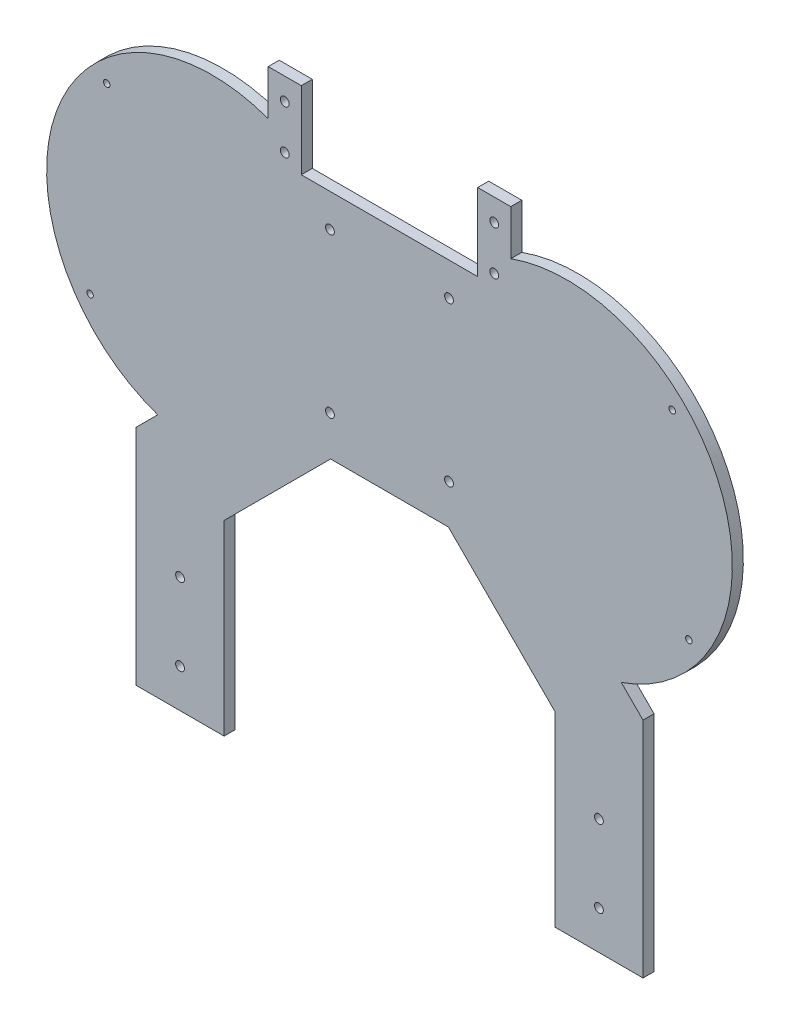
SolidWorks part; units mm, degrees
ref_plane "Front Plane" through (0, 0, 0) normal (0, 0, 1) x (1, 0, 0)
ref_plane "Top Plane" through (0, 0, 0) normal (0, 1, 0) x (1, 0, 0)
ref_plane "Right Plane" through (0, 0, 0) normal (1, 0, 0) x (0, 0, -1)
sketch "Sketch1" plane through (0, 0, 0) normal (0, 0, 1) x (1, 0, 0)
  line L1 (-100, -75) -> (100, -75)
  line L2 (-100, -75) -> (-100, 75)
  line L3 (-100, 75) -> (100, 75)
  line L4 (100, -75) -> (100, 75)
  line L5 (-100, -75) -> (100, 75) construction
  line L6 (-100, 75) -> (100, -75) construction
  line L8 (-47.5, 40) -> (47.5, 40) construction
  line L9 (0, 75) -> (0, -75) construction
  line L10 (-27, -52) -> (27, -52) construction
  line L11 (-27, -52) -> (-27, 20) construction
  line L12 (-27, 20) -> (27, 20) construction
  line L13 (27, -52) -> (27, 20) construction
  line L14 (-27, -52) -> (27, 20) construction
  line L15 (-27, 20) -> (27, -52) construction
  line L23 (-55, 70) -> (55, 70)
  line L24 (-55, 70) -> (-55, -70)
  line L25 (-55, -70) -> (55, -70)
  line L26 (55, 70) -> (55, -70)
  line L27 (-55, 70) -> (55, -70) construction
  line L28 (-55, -70) -> (55, 70) construction
  line L29 (-40, 70) -> (40, 70)
  line L30 (-40, 70) -> (-40, 35)
  line L31 (-40, 35) -> (40, 35)
  line L32 (40, 70) -> (40, 35)
  line L33 (-40, 70) -> (40, 35) construction
  line L34 (-40, 35) -> (40, 70) construction
  circle A2 centre (-47.5, 40) radius 2
  circle A3 centre (47.5, 40) radius 2
  circle A4 centre (-27, 20) radius 2
  circle A5 centre (27, 20) radius 2
  circle A6 centre (27, -52) radius 2
  circle A7 centre (-27, -52) radius 2
  circle A8 centre (-47.5, 60) radius 2
  circle A9 centre (47.5, 60) radius 2
  point P0 (0, 0)
  point P15 (0, 40)
  point P18 (0, -16)
  point P56 (0, 0)
  point P63 (0, 52.5)
  dimension "D3" = 4
  dimension "D4" = 20
  dimension "D5" = 4
  dimension "D8" = 4
  dimension "D1" = 150
  dimension "D2" = 200
  dimension "D6" = 72
  dimension "D7" = 54
  dimension "D14" = 30
  dimension "D15" = 140
  dimension "D16" = 110
  dimension "D17" = 95
  dimension "D18" = 20
  dimension "D19" = 35
  dimension "D20" = 80
extrude "Boss-Extrude1" add sketch "Sketch1" along normal blind 5 contours L23 L32 L31 L30 L24 L25 L26 A7 A6 A5 A4 A3 A2 | L2 L1 L4 L3
sketch "Sketch2" plane through (0, 0, 0) normal (0, 0, 1) x (1, 0, 0)
  line L0 (-55, -70) -> (-100.8579, -115.8579) construction
  line L1 (-55, 70) -> (-55, -70) construction
  line L2 (-55, -41.7157) -> (-115, -101.7157)
  line L3 (-26.7157, -70) -> (-86.7157, -130)
  line L4 (-55, -70) -> (55, -70) construction
  line L5 (-115, -101.7157) -> (-86.7157, -130)
  line L6 (-115, -101.7157) -> (-115, -203)
  line L7 (-75, -118.2843) -> (-75, -203)
  line L8 (-75, -203) -> (-115, -203)
  line L9 (0, 75) -> (0, -75) construction
  line L10 (-55, -41.7157) -> (-26.7157, -70)
  line L11 (-55, 70) -> (-55, -70) construction
  line L12 (-75, -203) -> (-115, -203) construction
  line L13 (-55, -70) -> (55, -70) construction
  line L14 (-55, 70) -> (-55, -70) construction
  circle A0 centre (-95, -150.5) radius 2
  circle A1 centre (-95, -185.5) radius 2
  dimension "D5" = 4
  dimension "D6" = 4
  dimension "D1" = 135
  dimension "D2" = 40
  dimension "D3" = 40
  dimension "D4" = 75
extrude "Boss-Extrude2" add sketch "Sketch2" along normal blind 5
mirror "Mirror1" about plane through (0, 0, 0) normal (1, 0, 0) of "Boss-Extrude2"
sketch "Sketch3" plane through (0, 0, 5) normal (0, 0, 1) x (1, 0, 0)
  line L0 (0, 0) -> (0, 95.843) construction
  line L1 (-80.5, -21) -> (-128.2297, 26.7297) construction
  line L2 (-80.5, -21) -> (-135.7928, -59.7164) construction
  line L3 (-80.5, -21) -> (-148, -21) construction
  line L4 (-42.1979, -85.4821) -> (-26.7157, -70)
  line L5 (-26.7157, -70) -> (-23.7197, -70)
  line L6 (-26.7157, -70) -> (26.7157, -70) construction
  line L7 (-26.7157, -70) -> (-75, -118.2843) construction
  line L8 (26.7157, -70) -> (23.7197, -70)
  line L9 (42.1979, -85.4821) -> (26.7157, -70)
  circle A0 centre (-80.5, -21) radius 60 construction
  circle A1 centre (-80.5, -21) radius 75
  circle A2 centre (-80.5, -21) radius 67.5 construction
  circle A3 centre (-128.2297, 26.7297) radius 1.4732
  circle A4 centre (-135.7928, -59.7164) radius 1.4732
  circle A5 centre (-47.5, 40) radius 2 construction
  circle A6 centre (135.7928, -59.7164) radius 1.4732
  circle A7 centre (128.2297, 26.7297) radius 1.4732
  circle A8 centre (80.5, -21) radius 75
  circle A9 centre (-47.5, 40) radius 2
  circle A10 centre (-27, 20) radius 2
  circle A11 centre (-27, -52) radius 2
  circle A12 centre (-27, 20) radius 2 construction
  circle A13 centre (-27, -52) radius 2 construction
  circle A14 centre (47.5, 40) radius 2
  circle A15 centre (27, 20) radius 2
  circle A16 centre (27, -52) radius 2
  point P44 (0, 0)
  line M5 (-26.7157, -70) -> (26.7157, -70)
  line M6 (26.7157, -70) -> (75, -118.2843)
  line M10 (115, -101.7157) -> (55, -41.7157)
  line M11 (55, -41.7157) -> (55, 70)
  line M13 (40, 70) -> (40, 35)
  line M14 (40, 35) -> (-40, 35)
  line M15 (-40, 35) -> (-40, 70)
  line M17 (-55, 70) -> (-55, -41.7157)
  line M18 (-55, -41.7157) -> (-115, -101.7157)
  line M22 (-75, -118.2843) -> (-26.7157, -70)
  circle M23 centre (-47.5, 40) radius 2
  circle M24 centre (47.5, 40) radius 2
  circle M25 centre (-27, 20) radius 2
  circle M26 centre (27, 20) radius 2
  circle M27 centre (27, -52) radius 2
  circle M28 centre (-27, -52) radius 2
  dimension "D1" = 120
  dimension "D3" = 7.5
  dimension "D4" = 61
  dimension "D8" = 2.9464
  dimension "D5" = 45
  dimension "D6" = 35
  dimension "D7" = 161
  dimension "D2" = 15
extrude "Boss-Extrude3" add sketch "Sketch3" against normal up to surface (5 mm away) contours A1 A4 A3 M17 M18 | A1 M15 M17 M18 M22 M5 M14 M28 M25 M23 | A8 M10 M11 M13 M14 M5 M6 M27 M26 M24 | A8 A6 A7 M11 M10 up to face at (0, -62.524, 0)
